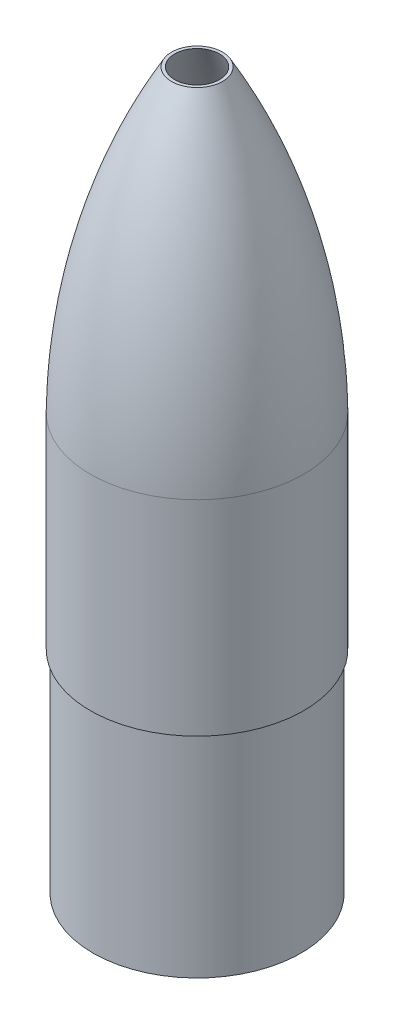
SolidWorks part; units mm, degrees
other "Markup1"
sketch "Sketch4" plane through (78.16, -154.2442, 78.16) normal (0.9651, -0.1718, 0.1975) x (-0.1686, -0.9851, -0.0334)
material "Thornel Mat VMA"
ref_plane "Front Plane" through (0, 0, 0) normal (0, 0, 1) x (1, 0, 0)
ref_plane "Top Plane" through (0, 0, 0) normal (0, 1, 0) x (1, 0, 0)
ref_plane "Right Plane" through (0, 0, 0) normal (1, 0, 0) x (0, 0, -1)
sketch "Sketch1" plane through (0, 0, 0) normal (0, 0, 1) x (1, 0, 0)
  line L0 (78.16, 0.5558) -> (78.16, 150.5558)
  line L3 (0, 0) -> (0, 614.1078) construction
  line L6 (0, -198.8179) -> (0, -350.074)
  line L7 (76.2, 0.5558) -> (76.2, 150.5443)
  line L8 (78.16, 0.5558) -> (76.2, 0.5558)
  line L9 (0, 400) -> (0, 396.4892)
  spline S0 degree 4 poles (-15.3468, 421.2955) (-15.0103, 420.856) (-14.3388, 419.9758) (-13.3353, 418.6515) (-12.0074, 416.8814) (-10.6914, 415.1091) (-9.395, 413.3458) (-8.1033, 411.5702) (-6.8448, 409.8242) (-5.5578, 408.0177) (-4.3521, 406.3128) (-3.0104, 404.3884) (-1.9663, 402.8848) (-0.427, 400.6308) (0.2737, 399.5978) (1.5381, 397.7184) (2.5222, 396.2406) (3.5056, 394.7509) (4.501, 393.2308) (5.4828, 391.7179) (6.46, 390.199) (7.4365, 388.6679) (8.4121, 387.1246) (16.4914, 374.2288) (28.348, 353.3444) (42.5411, 323.7528) (57.5292, 282.9984) (68.4498, 242.8729) (74.1096, 210.0768) (76.6559, 184.8086) (77.5185, 170.0675) (77.6804, 166.8514) (77.8002, 164.1053) (77.872, 162.2907) (77.9363, 160.4857) (77.9934, 158.6832) (78.0434, 156.8667) (78.0859, 155.0826) (78.1211, 153.3065) (78.1553, 151.0401) (78.1694, 149.7893) (78.1915, 147.0488) (78.1921, 145.2128) (78.1883, 142.8552) (78.1709, 140.7595) (78.1445, 138.5315) (78.1069, 136.371) (78.059, 134.1662) (78, 131.9694) (77.93, 129.7536) (77.8488, 127.533) (77.7798, 125.8658) (77.7301, 124.7552) (77.7044, 124.2) knots 0 0 0 0 0 0.006969 0.013937 0.020906 0.027875 0.034717 0.04156 0.048403 0.055246 0.062088 0.068931 0.075774 0.082616 0.0883 0.093983 0.099666 0.10535 0.111033 0.116716 0.122399 0.128083 0.133891 0.1397 0.313954 0.430124 0.546294 0.685698 0.836718 0.848335 0.865761 0.871569 0.877253 0.882936 0.888619 0.894302 0.899986 0.905669 0.911352 0.917035 0.923907 0.930779 0.93765 0.944522 0.951393 0.958265 0.965136 0.972008 0.979006 0.986004 0.993002 1 1 1 1 1 construction
  spline S1 degree 4 poles (0, 400) (0.2113, 399.6881) (0.6358, 399.0596) (1.5381, 397.7184) (2.5222, 396.2406) (3.5056, 394.7509) (4.501, 393.2308) (5.4828, 391.7179) (6.46, 390.199) (7.4365, 388.6679) (8.4121, 387.1246) (16.4914, 374.2288) (28.348, 353.3444) (42.5411, 323.7528) (57.5292, 282.9984) (68.4498, 242.8729) (74.1096, 210.0768) (76.6559, 184.8086) (77.5185, 170.0675) (77.6804, 166.8514) (77.8002, 164.1053) (77.872, 162.2907) (77.9363, 160.4857) (77.9934, 158.6832) (78.0434, 156.8667) (78.0859, 155.0826) (78.1211, 153.3065) (78.1455, 151.6911) (78.1556, 150.9325) (78.16, 150.5558) knots 0.082616 0.082616 0.082616 0.082616 0.082616 0.0883 0.093983 0.099666 0.10535 0.111033 0.116716 0.122399 0.128083 0.133891 0.1397 0.313954 0.430124 0.546294 0.685698 0.836718 0.848335 0.865761 0.871569 0.877253 0.882936 0.888619 0.894302 0.899986 0.905669 0.911352 0.917035 0.917035 0.917035 0.917035 0.917035
  spline S2 degree 1 poles (-1.6226, 398.9005) (76.2, 150.5443) knots 0 0 1 1 construction
  spline S3 degree 3 poles (-1.6226, 398.9005) (-1.4527, 398.6498) (-1.1386, 398.1849) (-0.5196, 397.2651) (0.1099, 396.3257) (0.6873, 395.459) (1.2483, 394.6123) (1.9995, 393.4729) (3.323, 391.4513) (5.1827, 388.5671) (9.5921, 381.5907) (18.7945, 366.2671) (36.7943, 332.2032) (57.0765, 280.9241) (69.6847, 227.2404) (74.343, 188.9958) (75.531, 171.161) (75.8913, 162.9157) (76.0101, 159.4861) (76.0769, 157.0706) (76.1102, 155.7062) (76.1328, 154.6907) (76.1533, 153.65) (76.1724, 152.5206) (76.189, 151.4097) (76.1964, 150.8476) (76.2, 150.5443) knots 0.082616 0.082616 0.082616 0.082616 0.085876 0.089135 0.092394 0.095654 0.098913 0.102172 0.108691 0.121728 0.134765 0.186913 0.29121 0.499804 0.708398 0.812695 0.864843 0.877881 0.890918 0.897436 0.900696 0.903955 0.907214 0.910473 0.913733 0.916992 0.916992 0.916992 0.916992 only from (0, 396.4892) to (76.2, 150.5443)
  point P11 (0, 400)
  dimension "D1" = 400
  dimension "D2" = 150
  dimension "D3" = 1.96
  dimension "D4" = 76.2
revolve "Revolve3" add sketch "Sketch1" angle 360 about L6
ref_plane "Plane1" through (0, 150.5558, 0) normal (0, 1, 0) x (1, 0, 0)
sketch "Sketch2" plane through (0, 150.5558, 0) normal (0, 1, 0) x (1, 0, 0)
  circle A0 centre (0, 0) radius 76.2 construction
  circle A1 centre (0, 0) radius 76.2
  circle A2 centre (0, 0) radius 73.2
  dimension "D1" = 3
extrude "Boss-Extrude1" add sketch "Sketch2" against normal blind 304.8
ref_plane "Plane2" through (0, 400, 0) normal (0, -1, 0) x (-1, 0, 0)
sketch "Sketch3" plane through (0, 400, 0) normal (0, -1, 0) x (-1, 0, 0)
  circle A0 centre (0, 0) radius 126.4604
extrude "Cut-Extrude1" cut sketch "Sketch3" along normal blind 30 contours A0
